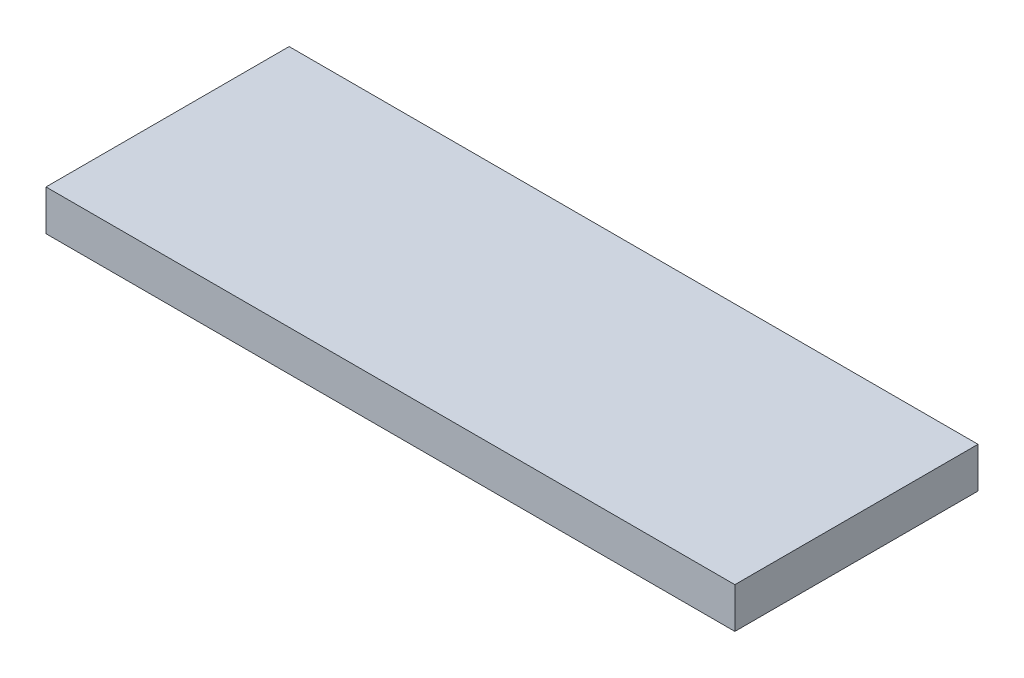
SolidWorks part; units mm, degrees
ref_plane "Front" through (0, 0, 0) normal (0, 0, 1) x (1, 0, 0)
ref_plane "Top" through (0, 0, 0) normal (0, 1, 0) x (1, 0, 0)
ref_plane "Right" through (0, 0, 0) normal (1, 0, 0) x (0, 0, -1)
sketch "Sketch1" plane through (0, 0, 0) normal (0, 1, 0) x (1, 0, 0)
  line L1 (0, 0) -> (85, 0)
  line L2 (0, 0) -> (0, 30)
  line L3 (0, 30) -> (85, 30)
  line L4 (85, 0) -> (85, 30)
  dimension "D1" = 30
  dimension "D2" = 85
extrude "Boss-Extrude1" add sketch "Sketch1" along normal blind 5
